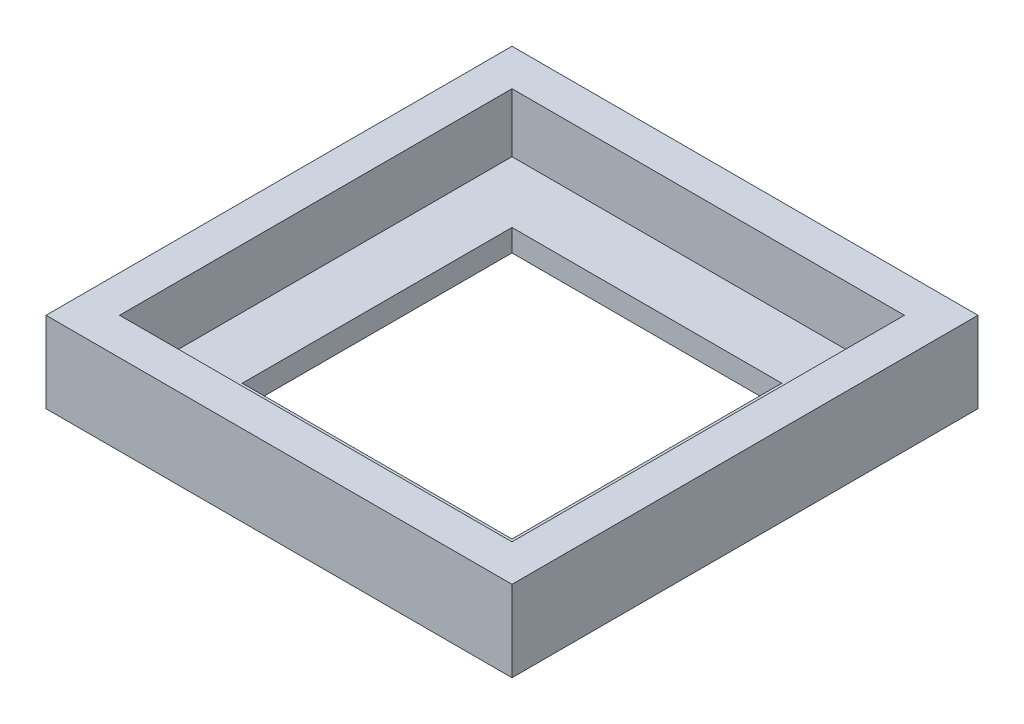
SolidWorks part; units mm, degrees
ref_plane "Front Plane" through (0, 0, 0) normal (0, 0, 1) x (1, 0, 0)
ref_plane "Top Plane" through (0, 0, 0) normal (0, 1, 0) x (1, 0, 0)
ref_plane "Right Plane" through (0, 0, 0) normal (1, 0, 0) x (0, 0, -1)
sketch "Sketch1" plane through (0, 0, 0) normal (0, 1, 0) x (1, 0, 0)
  line L0 (0, 0) -> (38, 0)
  line L1 (38, 0) -> (38, 38)
  line L2 (38, 38) -> (0, 38)
  line L3 (0, 38) -> (0, 0)
  line L4 (8, 8) -> (30, 8)
  line L5 (30, 8) -> (30, 30)
  line L6 (30, 30) -> (8, 30)
  line L7 (8, 30) -> (8, 8)
  point P8 (19, 8)
  point P10 (19, 0)
  point P11 (8, 19)
  point P12 (0, 19)
  dimension "D1" = 22
  dimension "D2" = 22
  dimension "D3" = 38
  dimension "D4" = 38
extrude "Boss-Extrude1" add sketch "Sketch1" along normal blind 1.8
sketch "Sketch2" plane through (0, 1.8, 0) normal (0, 1, 0) x (1, 0, 0)
  line L0 (0, 38) -> (0, 0) construction
  line L1 (38, 38) -> (0, 38) construction
  line L2 (38, 0) -> (38, 38) construction
  line L3 (0, 0) -> (38, 0) construction
  line L4 (0, 38) -> (0, 0)
  line L5 (38, 38) -> (0, 38)
  line L6 (38, 0) -> (38, 38)
  line L7 (0, 0) -> (38, 0)
  line L8 (3, 35) -> (3, 3)
  line L9 (3, 3) -> (35, 3)
  line L10 (35, 3) -> (35, 35)
  line L11 (35, 35) -> (3, 35)
  point P8 (35, 19)
  point P9 (38, 19)
  point P10 (19, 3)
  point P11 (19, 0)
  dimension "D1" = 32
extrude "Boss-Extrude2" add sketch "Sketch2" along normal blind 4.8
